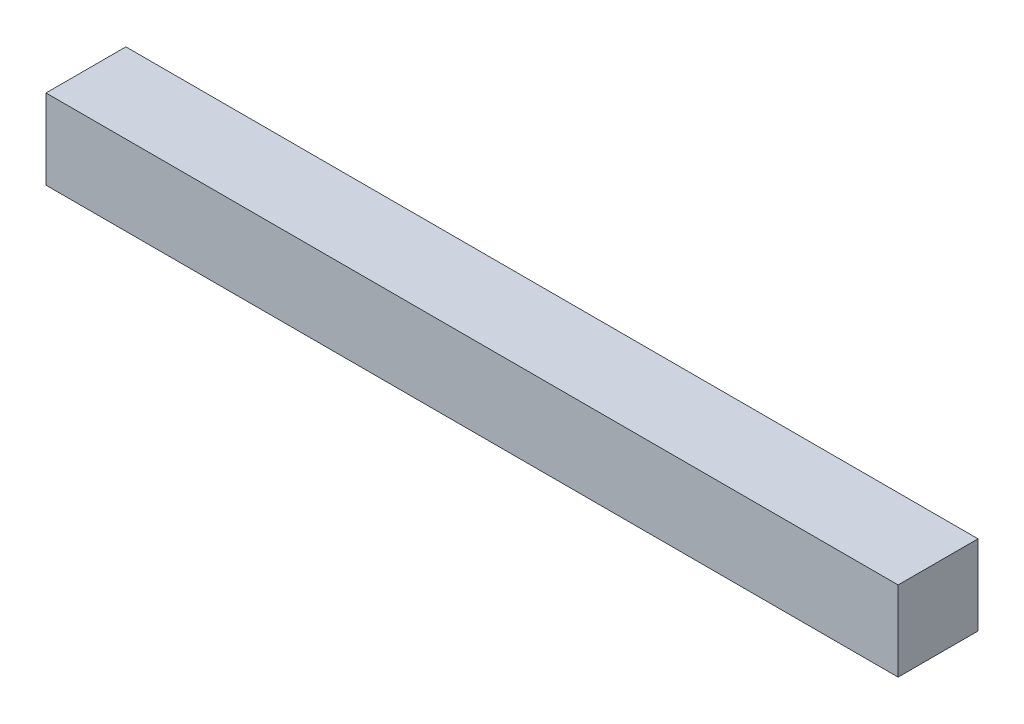
SolidWorks part; units mm, degrees
material "Pine"
ref_plane "Front Plane" through (0, 0, 0) normal (0, 0, 1) x (1, 0, 0)
ref_plane "Top Plane" through (0, 0, 0) normal (0, 1, 0) x (1, 0, 0)
ref_plane "Right Plane" through (0, 0, 0) normal (1, 0, 0) x (0, 0, -1)
sketch "Sketch1" plane through (0, 0, 0) normal (0, 0, 1) x (1, 0, 0)
  line L1 (-203.2, 19.05) -> (203.2, 19.05)
  line L2 (-203.2, 19.05) -> (-203.2, -19.05)
  line L3 (-203.2, -19.05) -> (203.2, -19.05)
  line L4 (203.2, 19.05) -> (203.2, -19.05)
  point P4 (0, 19.05)
  point P6 (203.2, 0)
  dimension "D1" = 406.4
  dimension "D2" = 38.1
extrude "Boss-Extrude1" add sketch "Sketch1" along normal blind 38.1
